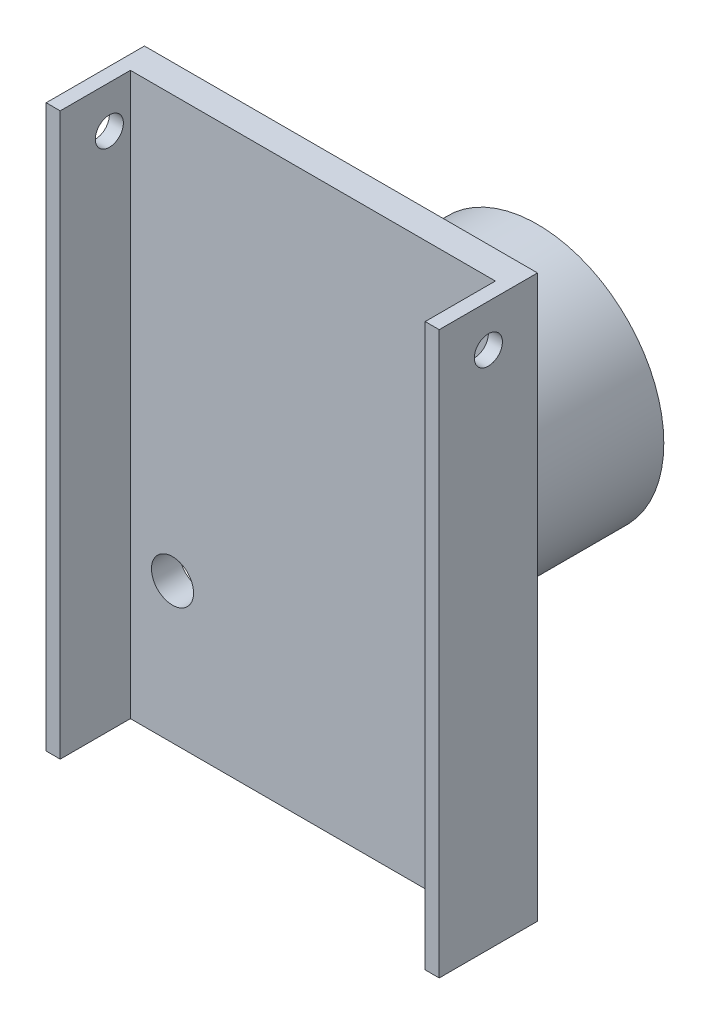
SolidWorks part; units mm, degrees
ref_plane "Front Plane" through (0, 0, 0) normal (0, 0, 1) x (1, 0, 0)
ref_plane "Top Plane" through (0, 0, 0) normal (0, 1, 0) x (1, 0, 0)
ref_plane "Right Plane" through (0, 0, 0) normal (1, 0, 0) x (0, 0, -1)
sketch "Sketch1" plane through (0, 0, 0) normal (0, 0, 1) x (1, 0, 0)
  line L1 (-70, 100) -> (70, 100)
  line L2 (-70, 100) -> (-70, -100)
  line L3 (-70, -100) -> (70, -100)
  line L4 (70, 100) -> (70, -100)
  line L5 (-70, 100) -> (70, -100) construction
  line L6 (-70, -100) -> (70, 100) construction
  circle A0 centre (-50, -50) radius 7.5
  circle A1 centre (50, -50) radius 7.5
  point P0 (0, 0)
  dimension "D3" = 15
  dimension "D4" = 15
  dimension "D1" = 140
  dimension "D2" = 200
  dimension "D5" = 20
  dimension "D6" = 50
  dimension "D7" = 50
  dimension "D8" = 20
extrude "Boss-Extrude1" add sketch "Sketch1" along normal blind 10
sketch "Sketch2" plane through (0, 0, 10) normal (0, 0, 1) x (1, 0, 0)
  line L0 (70, 100) -> (-70, 100) construction
  line L1 (-70, -100) -> (-65, -100)
  line L2 (-70, -100) -> (-70, 100)
  line L3 (-70, 100) -> (-65, 100)
  line L4 (-65, -100) -> (-65, 100)
  line L5 (-70, -100) -> (70, -100) construction
  line L6 (70, 100) -> (65, 100)
  line L7 (70, 100) -> (70, -100)
  line L8 (70, -100) -> (65, -100)
  line L9 (65, 100) -> (65, -100)
  dimension "D1" = 5
  dimension "D2" = 5
extrude "Boss-Extrude2" add sketch "Sketch2" along normal blind 25
sketch "Sketch3" plane through (-70, 0, 0) normal (-1, 0, 0) x (0, 0, 1)
  line L0 (0, 100) -> (0, -100) construction
  line L2 (35, 100) -> (0, 100) construction
  circle A0 centre (17.5, 85) radius 5
  dimension "D1" = 10
  dimension "D3" = 15
  dimension "D2" = 17.5
extrude "Cut-Extrude1" cut sketch "Sketch3" against normal through all
sketch "Sketch4" plane through (0, 0, 0) normal (0, 0, -1) x (-1, 0, 0)
  circle A0 centre (0, 0) radius 45
  circle A1 centre (0, 0) radius 35
  dimension "D1" = 90
  dimension "D2" = 70
extrude "Boss-Extrude3" add sketch "Sketch4" along normal blind 70
fillet "Fillet1" radius 10 1 edges at (45, 0, 0)
